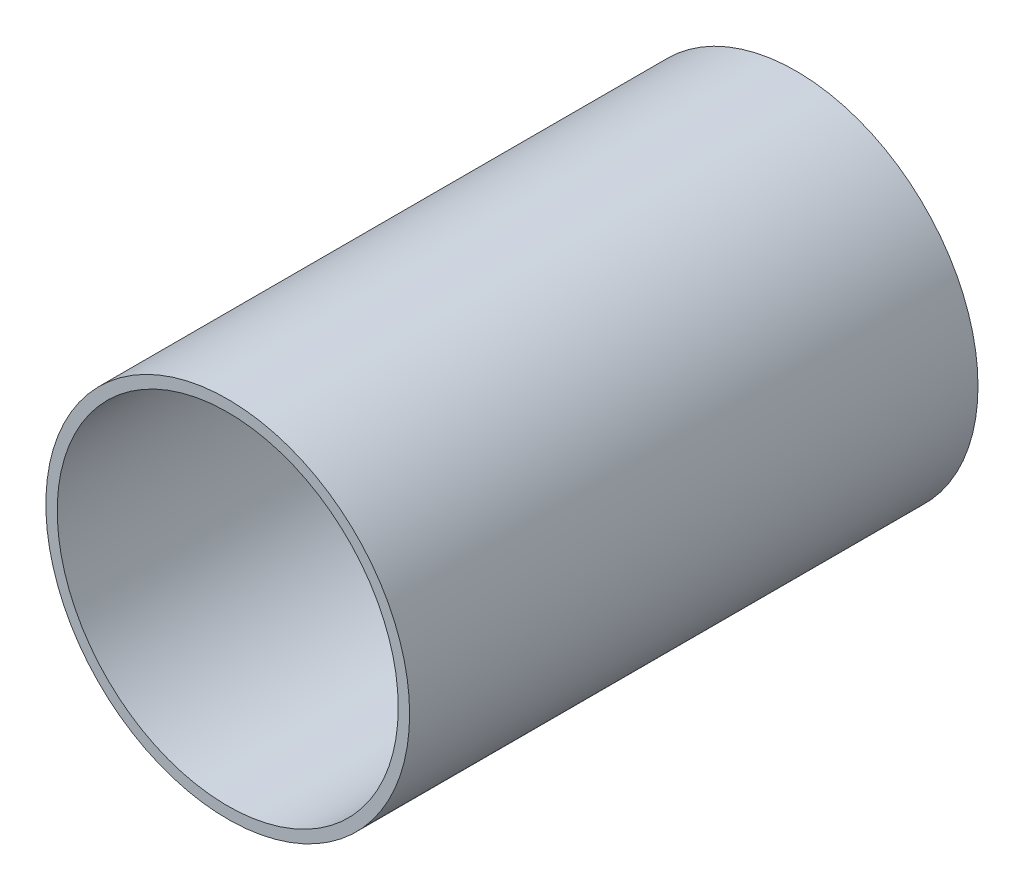
SolidWorks part; units mm, degrees
ref_plane "前视基准面" through (0, 0, 0) normal (0, 0, 1) x (1, 0, 0)
ref_plane "上视基准面" through (0, 0, 0) normal (0, 1, 0) x (1, 0, 0)
ref_plane "右视基准面" through (0, 0, 0) normal (1, 0, 0) x (0, 0, -1)
sketch "草图1" plane through (0, 0, 0) normal (0, 0, 1) x (1, 0, 0)
  circle A0 centre (0, 0) radius 30
extrude "拉伸-薄壁1" add sketch "草图1" along normal blind 100 thin
